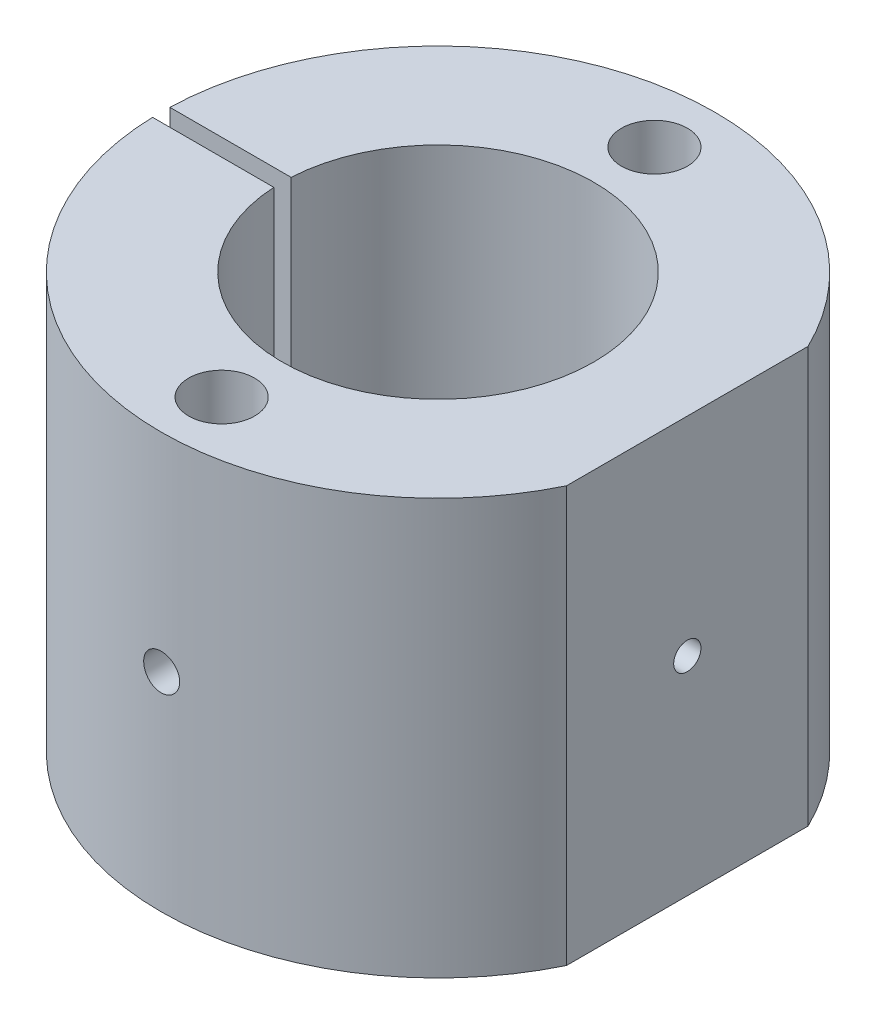
SolidWorks part; units mm, degrees
ref_plane "Front Plane" through (0, 0, 0) normal (0, 0, 1) x (1, 0, 0)
ref_plane "Top Plane" through (0, 0, 0) normal (0, 1, 0) x (1, 0, 0)
ref_plane "Right Plane" through (0, 0, 0) normal (1, 0, 0) x (0, 0, -1)
sketch "Sketch2" plane through (0, 0, 0) normal (0, 1, 0) x (1, 0, 0)
  circle A0 centre (0, 0) radius 14.2875
  circle A1 centre (0, 0) radius 25.4
  dimension "D1" = 50.8
  dimension "D2" = 28.575
extrude "Boss-Extrude1" add sketch "Sketch2" along normal blind 38.1
sketch "Sketch3" plane through (0, 38.1, 0) normal (0, 1, 0) x (1, 0, 0)
  line L0 (0, 0) -> (-25.4, 0) construction
  line L1 (0, 0.7937) -> (-25.4, 0.7937)
  line L2 (0, -0.7937) -> (-25.4, -0.7938)
  line L3 (-25.4, 0.7937) -> (-25.4, -0.7938)
  line L4 (0, 0.7937) -> (0, -0.7937)
  circle A0 centre (0, 0) radius 25.4 construction
  dimension "D1" = 0.7937
  dimension "D2" = 0.7937
extrude "Cut-Extrude1" cut sketch "Sketch3" against normal up to next
sketch "Sketch4" plane through (0, 38.1, 0) normal (0, 1, 0) x (1, 0, 0)
  line L0 (0, -14.2875) -> (0, -25.4) construction
  arc A0 (-14.2654, -0.7938) -> (-14.2654, 0.7937) centre (0, 0) ccw construction
  arc A1 (-25.3876, -0.7938) -> (-25.3876, 0.7937) centre (0, 0) ccw construction
  circle A2 centre (0, -19.8438) radius 3.0226
  dimension "D1" = 6.0452
extrude "Cut-Extrude2" cut sketch "Sketch4" against normal up to next
ref_plane "Plane1" through (0, 0, 25.4) normal (0, 0, 1) x (1, 0, 0)
sketch "Sketch9" plane through (0, 0, 0.7937) normal (0, 0, -1) x (-1, 0, 0)
  line L0 (19.8265, 0) -> (19.8265, 38.1) construction
  line L1 (14.2654, 0) -> (25.3876, 0) construction
  line L2 (25.3876, 38.1) -> (14.2654, 38.1) construction
  circle A0 centre (19.8265, 29.1092) radius 1.0697 construction
  circle A1 centre (19.8265, 8.904) radius 1.0697 construction
hole_wizard "Tap Drill for M4x0.7 Tap1" positions "3DSketch4" profile "Sketch10" hole size "M4x0.7" standard "ANSI Metric"
sketch3d "3DSketch4"
  point P0 (-19.8265, 29.1092, 0.7938)
  point P3 (-19.8265, 8.904, 0.7938)
sketch "Sketch10" plane through (-19.8265, 29.1092, 0.7938) normal (1, 0, 0) x (0, 1, 0)
  line L0 (0, 0) -> (0, 15.0829)
  line L1 (0, 15.0829) -> (1.65, 15.0829)
  line L2 (1.65, 15.0829) -> (1.65, 0)
  line L5 (1.65, 0) -> (0, 0)
  line L11 (0, -6.35) -> (0, 107.95) construction
  dimension "Thru Hole Dia." = 3.3
  dimension "Thru Hole Depth" = 15.0829
sketch "Sketch11" plane through (0, 0, 25.4) normal (0, 0, 1) x (1, 0, 0)
  line L0 (0.0062, 0) -> (0.0062, 38.1) construction
  line L1 (-25.3876, 0) -> (25.4, 0) construction
  line L2 (25.4, 38.1) -> (-25.3876, 38.1) construction
  circle A0 centre (0.0062, 19.05) radius 1.65
  dimension "D1" = 3.3
extrude "Cut-Extrude5" cut sketch "Sketch11" against normal up to next
mirror "Mirror1" about plane through (0, 0, 0) normal (0, 0, 1) of "Cut-Extrude2", "Cut-Extrude5"
sketch "Sketch12" plane through (0, 38.1, 0) normal (0, 1, 0) x (1, 0, 0)
  line L0 (22.86, 11.0716) -> (22.86, -11.0716)
  arc A0 (-25.3876, -0.7938) -> (-25.3876, 0.7937) centre (0, 0) ccw construction
  arc A1 (22.86, -11.0716) -> (22.86, 11.0716) centre (0, 0) ccw
  arc A2 (-14.2654, -0.7938) -> (-14.2654, 0.7937) centre (0, 0) ccw construction
  dimension "D1" = 22.86
extrude "Cut-Extrude6" cut sketch "Sketch12" against normal up to next
sketch "Sketch13" plane through (22.86, 0, 0) normal (1, 0, 0) x (0, 0, -1)
  line L0 (0, 38.1) -> (0, 0) construction
  line L1 (11.0716, 38.1) -> (-11.0716, 38.1) construction
  line L2 (-11.0716, 0) -> (11.0716, 0) construction
  circle A0 centre (0, 19.05) radius 1.15 construction
  dimension "D1" = 2.3
hole_wizard "Tap Drill for M3x0.5 Tap2" positions "3DSketch5" profile "Sketch14" hole size "M3x0.5" standard "ANSI Metric"
sketch3d "3DSketch5"
  point P0 (22.86, 19.05, 0)
sketch "Sketch14" plane through (22.86, 19.05, 0) normal (0, 1, 0) x (0, 0, -1)
  line L0 (0, 0) -> (0, 5.3231)
  line L1 (0, 5.3231) -> (1.25, 4.572)
  line L2 (1.25, 4.572) -> (1.25, 0)
  line L5 (1.25, 0) -> (0, 0)
  line L10 (0, 5.3231) -> (-1.25, 4.572) construction
  line L11 (0, -6.35) -> (0, 107.95) construction
  dimension "Hole Dia." = 2.5
  dimension "Hole Depth" = 4.572
  dimension "Drill Angle" = 118
sketch "Sketch15" plane through (0, 0, 0.7937) normal (0, 0, -1) x (-1, 0, 0)
  line L0 (19.8265, 0) -> (19.8265, 38.1) construction
  line L1 (19.8265, 0) -> (19.8265, 38.1) construction
  circle A0 centre (19.8265, 19.05) radius 2.665
  dimension "D1" = 5.33
hole_wizard "Tap Drill for M5x0.8 Tap1" positions "3DSketch7" profile "Sketch17" hole size "M5x0.8" standard "ANSI Metric"
sketch3d "3DSketch7"
  point P0 (-19.8265, 19.05, 0.7938)
sketch "Sketch17" plane through (-19.8265, 19.05, 0.7938) normal (1, 0, 0) x (0, 1, 0)
  line L0 (0, 0) -> (0, 15.0829)
  line L1 (0, 15.0829) -> (2.1, 15.0829)
  line L2 (2.1, 15.0829) -> (2.1, 0)
  line L5 (2.1, 0) -> (0, 0)
  line L11 (0, -6.35) -> (0, 107.95) construction
  dimension "Thru Hole Dia." = 4.2
  dimension "Thru Hole Depth" = 15.0829
extrude "Cut-Extrude7" cut sketch "Sketch15" along normal through all
ref_plane "Plane2" through (0, 0, -8.7937) normal (0, 0, 1) x (1, 0, 0)
sketch "Sketch19" plane through (0, 0, -8.7937) normal (0, 0, 1) x (1, 0, 0)
  circle A0 centre (-19.8265, 19.05) radius 5
  dimension "D1" = 10
extrude "Cut-Extrude8" cut sketch "Sketch19" against normal up to next
